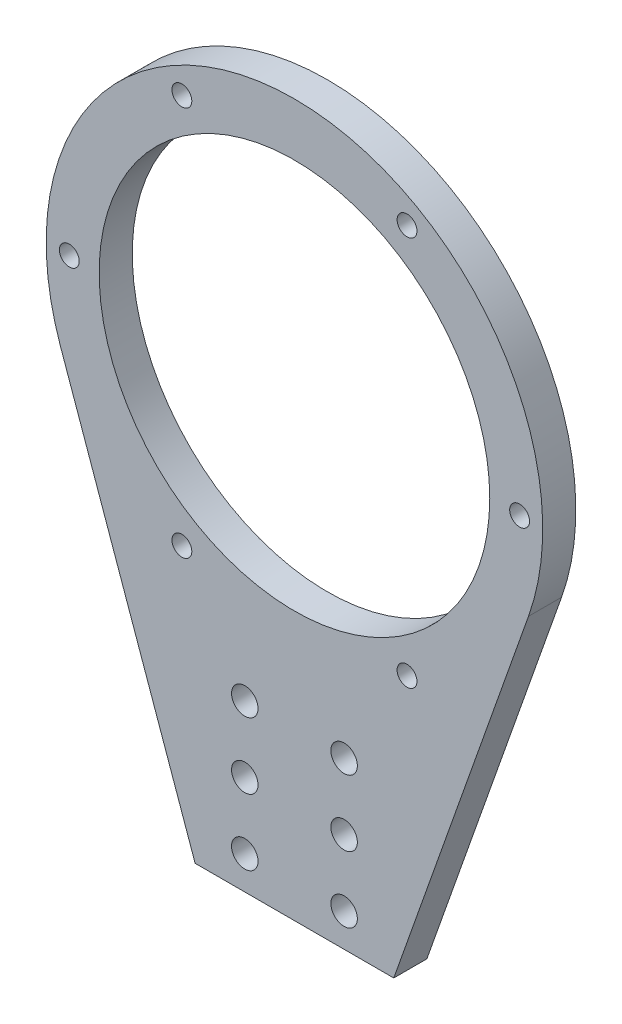
SolidWorks part; units mm, degrees
material "Acrylic (Medium-high impact)"
ref_plane "Front Plane" through (0, 0, 0) normal (0, 0, 1) x (1, 0, 0)
ref_plane "Top Plane" through (0, 0, 0) normal (0, 1, 0) x (1, 0, 0)
ref_plane "Right Plane" through (0, 0, 0) normal (1, 0, 0) x (0, 0, -1)
sketch "Sketch1" plane through (0, 0, 0) normal (0, 0, 1) x (1, 0, 0)
  line L0 (0, 0) -> (0, -75.7544) construction
  line L1 (-15, -70) -> (15, -70)
  line L4 (15, -70) -> (35.3503, -12.5142)
  line L5 (-15, -70) -> (-35.3503, -12.5142)
  line L6 (-35.3503, -12.5142) -> (0, 0) construction
  line L7 (0, 0) -> (35.3503, -12.5142) construction
  circle A0 centre (0, 0) radius 29.5
  circle A1 centre (0, 0) radius 37.5
  arc A2 (-35.3503, -12.5142) -> (35.3503, -12.5142) centre (0, 0) ccw
  dimension "D1" = 30
  dimension "D2" = 75
  dimension "D3" = 59
  dimension "D4" = 70
  dimension "D6" = 15
extrude "Boss-Extrude1" add sketch "Sketch1" along normal blind 5
sketch "Sketch9" plane through (0, 0, 5) normal (0, 0, 1) x (1, 0, 0)
  line L0 (60.1553, 0) -> (-60.1553, 0) construction
  line L1 (-60.1553, 0) -> (0, 0) construction
  line L2 (0, 0) -> (27.4803, 47.5973) construction
  line L3 (27.4803, 47.5973) -> (-28.626, -49.5817) construction
  line L4 (-28.626, -49.5817) -> (0, 0) construction
  line L5 (-29.2217, 50.6135) -> (0, 0) construction
  line L6 (0, 0) -> (29.2328, -50.6327) construction
  circle A0 centre (0, 0) radius 34.01 construction
  circle A1 centre (17.005, 29.4535) radius 1.5
  circle A2 centre (34.01, 0) radius 1.5
  circle A3 centre (17.005, -29.4535) radius 1.5
  circle A4 centre (-17.005, -29.4535) radius 1.5
  circle A5 centre (-34.01, 0) radius 1.5
  circle A6 centre (-17.005, 29.4535) radius 1.5
  dimension "D1" = 60
  dimension "D2" = 60
extrude "Cut-Extrude5" cut sketch "Sketch9" against normal blind 7
sketch "Sketch10" plane through (0, 0, 5) normal (0, 0, 1) x (1, 0, 0)
  line L0 (0, 0) -> (0, -98.5039) construction
  line L2 (-15, -70) -> (15, -70) construction
  circle A1 centre (7.5, -55) radius 2
  circle A2 centre (7.5, -65) radius 2
  circle A3 centre (-7.5, -65) radius 2
  circle A4 centre (-7.5, -55) radius 2
  circle A6 centre (0, 0) radius 37.5 construction
  circle A7 centre (-7.5, -45) radius 2
  circle A8 centre (7.5, -45) radius 2
  dimension "D2" = 10
  dimension "D3" = 7.5
  dimension "D4" = 7.5
  dimension "D5" = 7.5
  dimension "D6" = 7.5
  dimension "D7" = 5
  dimension "D8" = 10
  dimension "D9" = 10
  dimension "D10" = 5
  dimension "D11" = 10
extrude "Cut-Extrude6" cut sketch "Sketch10" against normal blind 7
